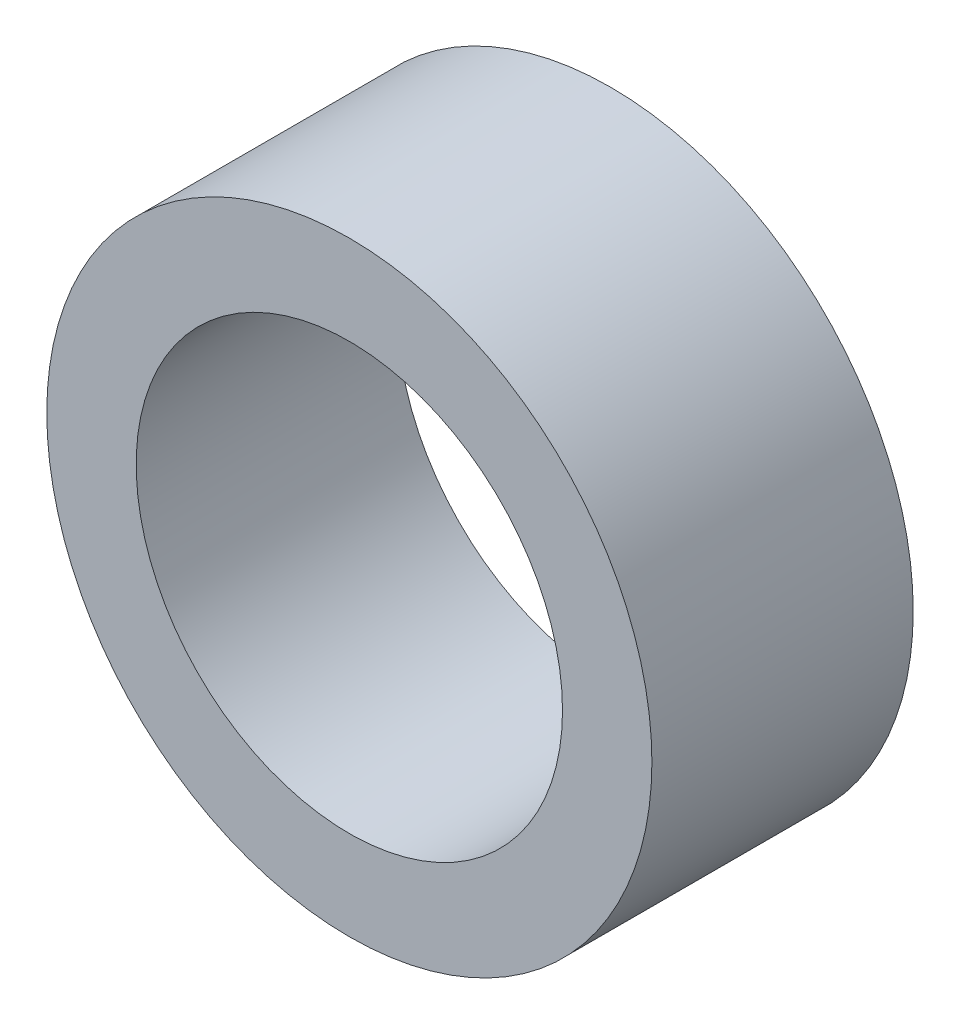
SolidWorks part; units mm, degrees
ref_plane "Front Plane" through (0, 0, 0) normal (0, 0, 1) x (1, 0, 0)
ref_plane "Top Plane" through (0, 0, 0) normal (0, 1, 0) x (1, 0, 0)
ref_plane "Right Plane" through (0, 0, 0) normal (1, 0, 0) x (0, 0, -1)
sketch "Sketch1" plane through (0, 0, 0) normal (0, 0, 1) x (1, 0, 0)
  circle A0 centre (0, 0) radius 22
  circle A1 centre (0, 0) radius 15.5
extrude "Bearing envelope - 31 mm ID x 44 mm OD" add sketch "Sketch1" along normal blind 19 from offset 23
